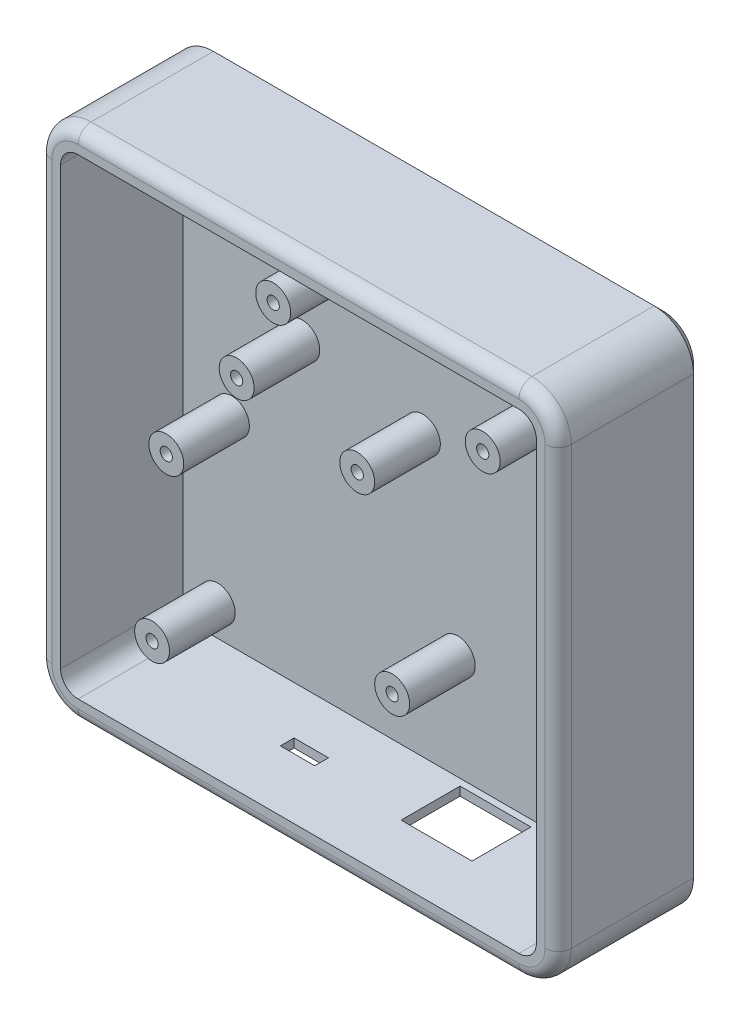
SolidWorks part; units mm, degrees
ref_plane "Front Plane" through (0, 0, 0) normal (0, 0, 1) x (1, 0, 0)
ref_plane "Top Plane" through (0, 0, 0) normal (0, 1, 0) x (1, 0, 0)
ref_plane "Right Plane" through (0, 0, 0) normal (1, 0, 0) x (0, 0, -1)
sketch "Sketch1" plane through (0, 0, 0) normal (0, 0, 1) x (1, 0, 0)
  line L8 (28.6312, 52.5) -> (28.6312, -47.5)
  line L9 (28.6312, 52.5) -> (28.6312, -47.5)
  line L10 (32.6312, -51.5) -> (133.6312, -51.5)
  line L12 (23.6312, 52.5) -> (23.6312, -47.5)
  line L13 (23.6312, 52.5) -> (23.6312, -47.5)
  line L14 (32.6312, -51.5) -> (133.6312, -51.5)
  line L16 (137.6312, -47.5) -> (137.6312, 52.5)
  line L17 (32.6312, -56.5) -> (133.6312, -56.5)
  line L19 (137.6312, -47.5) -> (137.6312, 52.5)
  line L20 (133.6312, 56.5) -> (32.6312, 56.5)
  line L21 (133.6312, 56.5) -> (32.6312, 56.5)
  line L33 (32.6312, -56.5) -> (133.6312, -56.5)
  line L34 (142.6312, -47.5) -> (142.6312, 52.5)
  line L35 (142.6312, -47.5) -> (142.6312, 52.5)
  line L36 (133.6312, 61.5) -> (32.6312, 61.5)
  line L37 (133.6312, 61.5) -> (32.6312, 61.5)
  arc A8 (28.6312, -47.5) -> (32.6312, -51.5) centre (32.6312, -47.5) ccw
  arc A9 (28.6312, -47.5) -> (32.6312, -51.5) centre (32.6312, -47.5) ccw
  arc A10 (133.6312, -51.5) -> (137.6312, -47.5) centre (133.6312, -47.5) ccw
  arc A11 (133.6312, -51.5) -> (137.6312, -47.5) centre (133.6312, -47.5) ccw
  arc A12 (137.6312, 52.5) -> (133.6312, 56.5) centre (133.6312, 52.5) ccw
  arc A13 (137.6312, 52.5) -> (133.6312, 56.5) centre (133.6312, 52.5) ccw
  arc A14 (32.6312, 56.5) -> (28.6312, 52.5) centre (32.6312, 52.5) ccw
  arc A15 (32.6312, 56.5) -> (28.6312, 52.5) centre (32.6312, 52.5) ccw
  arc A16 (23.6312, -47.5) -> (32.6312, -56.5) centre (32.6312, -47.5) ccw
  arc A17 (23.6312, -47.5) -> (32.6312, -56.5) centre (32.6312, -47.5) ccw
  arc A18 (133.6312, -56.5) -> (142.6312, -47.5) centre (133.6312, -47.5) ccw
  arc A19 (133.6312, -56.5) -> (142.6312, -47.5) centre (133.6312, -47.5) ccw
  arc A20 (142.6312, 52.5) -> (133.6312, 61.5) centre (133.6312, 52.5) ccw
  arc A21 (142.6312, 52.5) -> (133.6312, 61.5) centre (133.6312, 52.5) ccw
  arc A22 (32.6312, 61.5) -> (23.6312, 52.5) centre (32.6312, 52.5) ccw
  arc A23 (32.6312, 61.5) -> (23.6312, 52.5) centre (32.6312, 52.5) ccw
  dimension "D1" = 0
  dimension "D2" = 5
extrude "Boss-Extrude1" add sketch "Sketch1" against normal blind 28
sketch "Sketch2" plane through (0, 0, -28) normal (0, 0, -1) x (-1, 0, 0)
  circle A2 centre (-112.3812, 31) radius 4
  circle A3 centre (-64.3812, 36.5) radius 4
  circle A4 centre (-56.0062, 17.375) radius 4
  circle A5 centre (-83.6312, 12.5) radius 4
  circle A6 centre (-39.8812, -5.75) radius 4
  circle A7 centre (-36.6312, -44.5) radius 4
  circle A8 centre (-130.6312, -44.5) radius 4
  circle A9 centre (-91.6312, -27.5) radius 4
extrude "Boss-Extrude2" add sketch "Sketch2" against normal up to surface (15.0446 mm away) separate body
sketch "Sketch6" plane through (0, 0, -28) normal (0, 0, -1) x (-1, 0, 0)
  line L4 (-32.6312, 61.5) -> (-133.6312, 61.5)
  line L6 (-23.6312, -47.5) -> (-23.6312, 52.5)
  line L7 (-23.6312, -47.5) -> (-23.6312, 52.5)
  line L8 (-32.6312, 61.5) -> (-133.6312, 61.5)
  line L9 (-142.6312, 52.5) -> (-142.6312, -47.5)
  line L10 (-142.6312, 52.5) -> (-142.6312, -47.5)
  line L11 (-133.6312, -56.5) -> (-32.6312, -56.5)
  line L12 (-133.6312, -56.5) -> (-32.6312, -56.5)
  arc A4 (-32.6312, -56.5) -> (-23.6312, -47.5) centre (-32.6312, -47.5) ccw
  arc A5 (-32.6312, -56.5) -> (-23.6312, -47.5) centre (-32.6312, -47.5) ccw
  arc A6 (-23.6312, 52.5) -> (-32.6312, 61.5) centre (-32.6312, 52.5) ccw
  arc A7 (-23.6312, 52.5) -> (-32.6312, 61.5) centre (-32.6312, 52.5) ccw
  arc A8 (-133.6312, 61.5) -> (-142.6312, 52.5) centre (-133.6312, 52.5) ccw
  arc A9 (-133.6312, 61.5) -> (-142.6312, 52.5) centre (-133.6312, 52.5) ccw
  arc A10 (-142.6312, -47.5) -> (-133.6312, -56.5) centre (-133.6312, -47.5) ccw
  arc A11 (-142.6312, -47.5) -> (-133.6312, -56.5) centre (-133.6312, -47.5) ccw
  dimension "D1" = 0
extrude "Boss-Extrude4" add sketch "Sketch6" along normal blind 5
chamfer "Chamfer1" distance 2 angle 45 8 edges at (23.6312, 2.5, -33) (83.1312, -56.5, -33) (139.9952, -53.864, -33) (142.6312, 2.5, -33) (139.9952, 58.864, -33) (83.1312, 61.5, -33) (26.2672, 58.864, -33) (26.2672, -53.864, -33)
sketch "Sketch8" plane through (0, -56.5, 0) normal (0, 1, 0) x (1, 0, 0)
  line L10 (93.6824, 26.4647) -> (109.9274, 26.4647)
  line L11 (109.9274, 26.4647) -> (109.9274, 12.9554)
  line L12 (109.9274, 12.9554) -> (93.6874, 12.9554)
  line L13 (93.6874, 12.9554) -> (93.6824, 26.4647)
  line L14 (65.1152, 17) -> (73, 17)
  line L15 (73, 17) -> (73, 13.8557)
  line L16 (73, 13.8557) -> (65.1152, 13.8557)
  line L17 (65.1152, 13.8557) -> (65.1152, 17)
extrude "Cut-Extrude4" cut sketch "Sketch8" along normal blind 10
sketch "Sketch9" plane through (0, 0, -12.9554) normal (0, 0, 1) x (1, 0, 0)
  circle A0 centre (130.6312, -44.5) radius 1.4
  circle A1 centre (36.6312, -44.5) radius 1.4
  circle A2 centre (91.6312, -27.5) radius 1.4
  circle A3 centre (83.6312, 12.5) radius 1.4
  circle A4 centre (56.0062, 17.375) radius 1.4
  circle A5 centre (39.8812, -5.75) radius 1.4
  circle A6 centre (112.3812, 31) radius 1.4
  circle A7 centre (64.3812, 36.5) radius 1.4
extrude "Cut-Extrude5" cut sketch "Sketch9" against normal up to surface (15.0446 mm away)
fillet "Fillet1" radius 3 8 edges at (139.9952, -53.864, 0) (83.1312, -56.5, 0) (26.2672, -53.864, 0) (23.6312, 2.5, 0) (26.2672, 58.864, 0) (83.1312, 61.5, 0) (139.9952, 58.864, 0) (142.6312, 2.5, 0)
chamfer "Chamfer2" distance 3 angle 55 8 edges at (109.9274, -56.5, -19.7101) (101.8049, -56.5, -26.4647) (101.8074, -56.5, -12.9554) (93.6849, -56.5, -19.7101) (69.0576, -56.5, -17) (73, -56.5, -15.4279) (69.0576, -56.5, -13.8557) (65.1152, -56.5, -15.4279)
